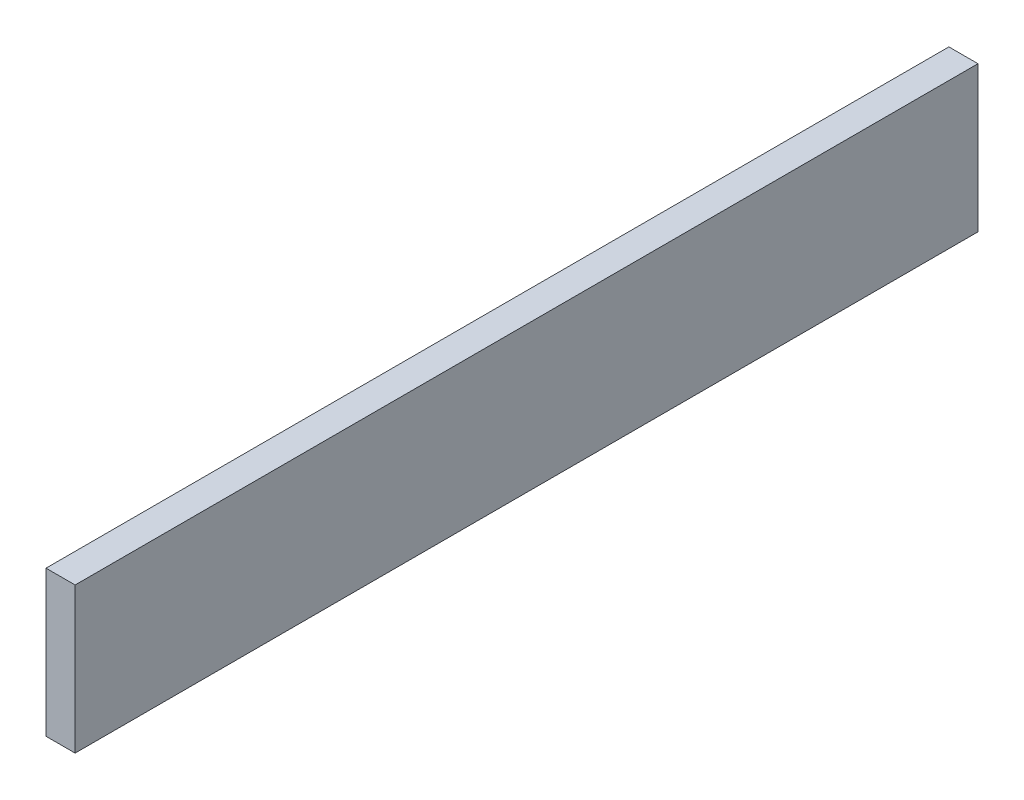
SolidWorks part; units mm, degrees
ref_plane "Front Plane" through (0, 0, 0) normal (0, 0, 1) x (1, 0, 0)
ref_plane "Top Plane" through (0, 0, 0) normal (0, 1, 0) x (1, 0, 0)
ref_plane "Right Plane" through (0, 0, 0) normal (1, 0, 0) x (0, 0, -1)
sketch "Sketch1" plane through (0, 0, 0) normal (1, 0, 0) x (0, 0, -1)
  line L1 (0, 0) -> (393.7, 0)
  line L2 (0, 0) -> (0, 63.5)
  line L3 (0, 63.5) -> (393.7, 63.5)
  line L4 (393.7, 0) -> (393.7, 63.5)
  dimension "D1" = 393.7
  dimension "D2" = 63.5
extrude "Boss-Extrude1" add sketch "Sketch1" along normal blind 12.7
